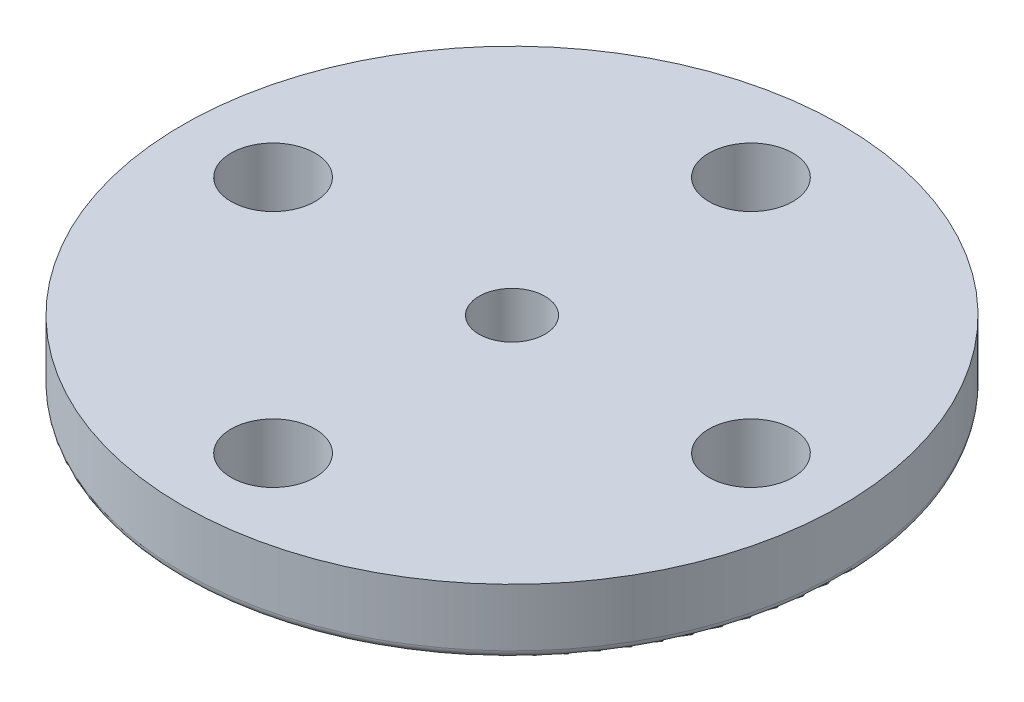
SolidWorks part; units mm, degrees
material "ABS"
ref_plane "Front Plane" through (0, 0, 0) normal (0, 0, 1) x (1, 0, 0)
ref_plane "Top Plane" through (0, 0, 0) normal (0, 1, 0) x (1, 0, 0)
ref_plane "Right Plane" through (0, 0, 0) normal (1, 0, 0) x (0, 0, -1)
sketch "Sketch1" plane through (0, 0, 0) normal (0, 1, 0) x (1, 0, 0)
  circle A0 centre (0, 0) radius 10
  dimension "D1" = 20
extrude "Boss-Extrude1" add sketch "Sketch1" along normal blind 2
sketch "Sketch2" plane through (0, 0, 0) normal (0, 1, 0) x (1, 0, 0)
  circle A0 centre (0, 0) radius 4.5
  dimension "D1" = 9
extrude "Boss-Extrude2" add sketch "Sketch2" against normal blind 2.5
sketch "Sketch3" plane through (0, 0, 0) normal (0, 1, 0) x (1, 0, 0)
  line L0 (0, 16.6668) -> (0, -17.2828) construction
  line L1 (-21.9372, 0) -> (30.2192, 0) construction
  line L2 (-7.25, 16.6668) -> (-7.25, -16.6668) construction
  line L3 (-15.9139, 7.25) -> (17.4197, 7.25) construction
  circle A0 centre (0, 7.25) radius 1.275
  circle A1 centre (-7.25, 0) radius 1.275
  circle A2 centre (0, -7.25) radius 1.275
  circle A3 centre (7.25, 0) radius 1.275
  dimension "D3" = 2.55
  dimension "D4" = 2.55
  dimension "D1" = 7.25
  dimension "D2" = 7.25
extrude "Cut-Extrude1" cut sketch "Sketch3" along normal through all
cosmetic thread "Cosmetic Thread1" parameters "D2"=2.87
cosmetic thread "Cosmetic Thread2" parameters "D2"=2.87
cosmetic thread "Cosmetic Thread3" parameters "D2"=2.87
cosmetic thread "Cosmetic Thread4" parameters "D2"=2.87
fillet "Fillet1" radius 0.25 1 edges at (0, 0, 10)
sketch "Sketch6" plane through (0, 2, 0) normal (0, 1, 0) x (1, 0, 0)
  circle A0 centre (0, 0) radius 1
  dimension "D1" = 2
extrude "Cut-Extrude2" cut sketch "Sketch6" against normal through all
sketch "Sketch7" plane through (0, -2.5, 0) normal (0, -1, 0) x (1, 0, 0)
  circle A0 centre (0, 0) radius 2.9
  dimension "D1" = 5.8
extrude "Cut-Extrude3" cut sketch "Sketch7" against normal blind 2.5
sketch3d "3DSketch1"
  line L0 (0, 0, 0) -> (0, -47.4119, 0) construction
